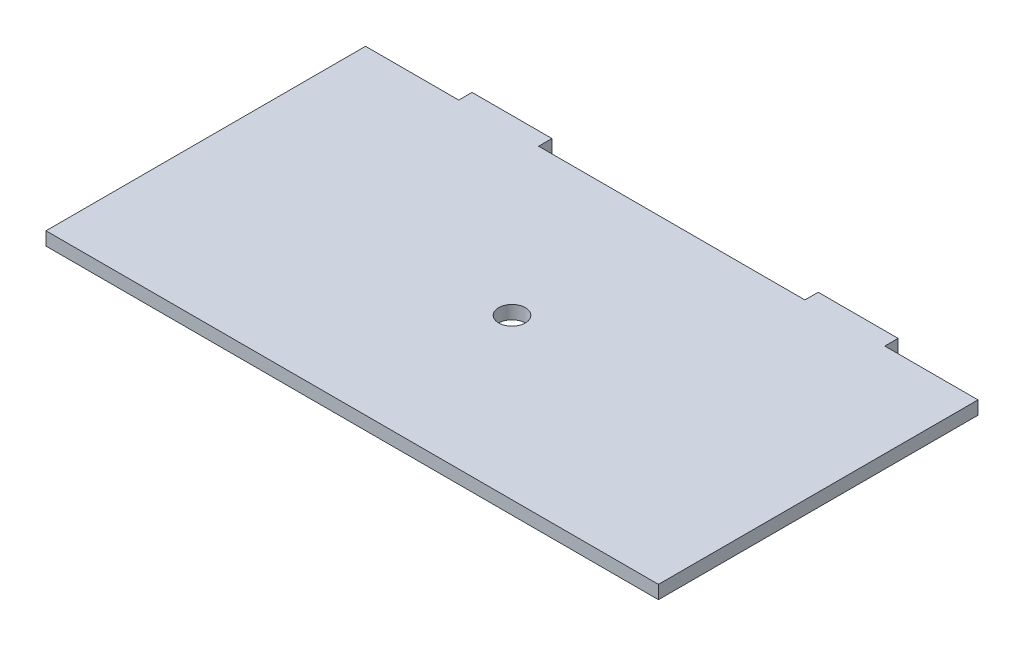
SolidWorks part; units mm, degrees
ref_plane "Front Plane" through (0, 0, 0) normal (0, 0, 1) x (1, 0, 0)
ref_plane "Top Plane" through (0, 0, 0) normal (0, 1, 0) x (1, 0, 0)
ref_plane "Right Plane" through (0, 0, 0) normal (1, 0, 0) x (0, 0, -1)
sketch "Sketch1" plane through (0, 0, 0) normal (0, 1, 0) x (1, 0, 0)
  line L0 (41.275, 76.2) -> (104.775, 76.2)
  line L1 (0, 0) -> (146.05, 0)
  line L2 (0, 0) -> (0, 76.2)
  line L3 (0, 76.2) -> (22.225, 76.2)
  line L4 (146.05, 0) -> (146.05, 76.2)
  line L5 (123.825, 76.2) -> (146.05, 76.2)
  line L6 (22.225, 76.2) -> (22.225, 79.375)
  line L7 (22.225, 79.375) -> (41.275, 79.375)
  line L8 (41.275, 76.2) -> (41.275, 79.375)
  line L10 (104.775, 76.2) -> (104.775, 79.375)
  line L11 (104.775, 79.375) -> (123.825, 79.375)
  line L12 (123.825, 76.2) -> (123.825, 79.375)
  circle A0 centre (73.025, 38.1) radius 3.175
  dimension "D5" = 6.35
  dimension "D1" = 76.2
  dimension "D2" = 146.05
  dimension "D3" = 73.025
  dimension "D4" = 38.1
  dimension "D6" = 22.225
  dimension "D7" = 3.175
  dimension "D8" = 19.05
  dimension "D9" = 19.05
  dimension "D10" = 3.175
  dimension "D11" = 22.225
extrude "Boss-Extrude1" add sketch "Sketch1" along normal blind 3.175
